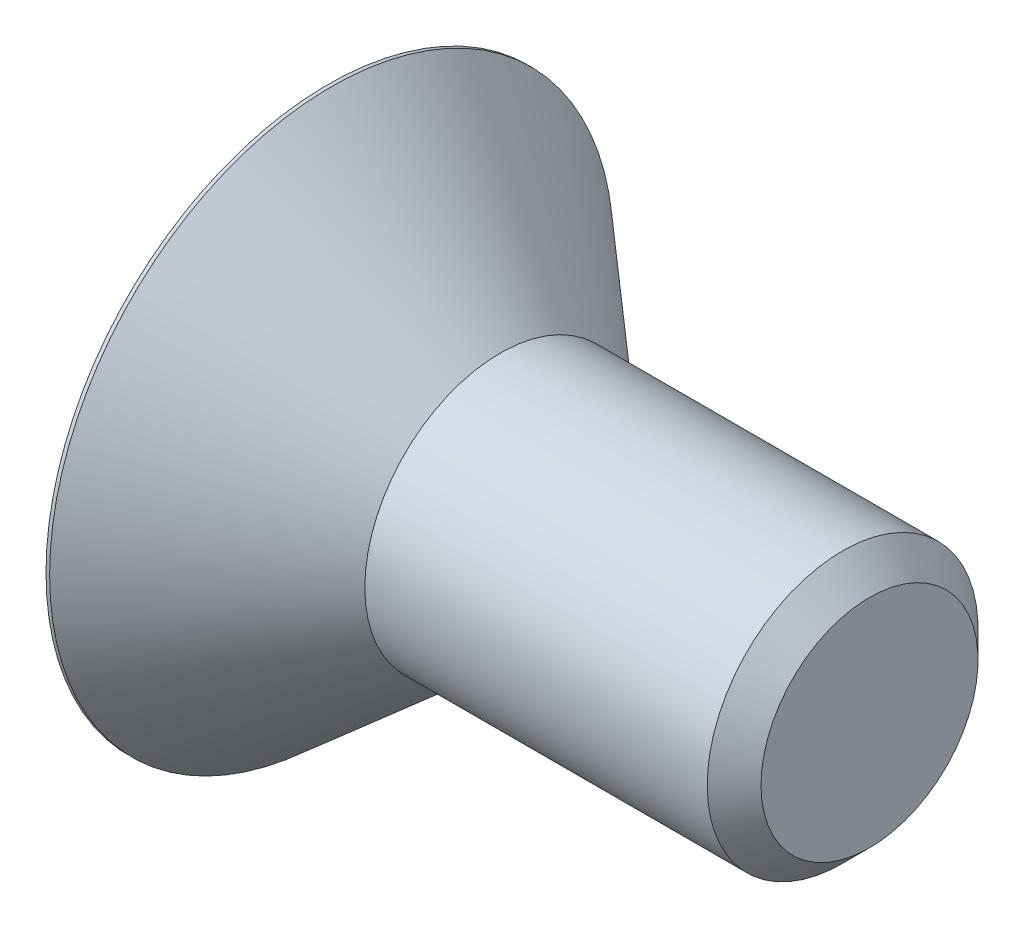
SolidWorks part; units mm, degrees
ref_plane "Plane1"
ref_plane "Plane2" through (0, 0, 0) normal (0, 1, 0) x (1, 0, 0)
ref_plane "Plane3" through (0, 0, 0) normal (1, 0, 0) x (0, 0, -1)
sketch "BodySke" plane through (0, 0, 0) normal (0, 0, 1) x (1, 0, 0)
  line L0 (0, 0) -> (0, 9.9187)
  line L1 (0.127, 9.9187) -> (6.0585, 4.7625)
  line L2 (0, 9.9187) -> (0.127, 9.9187)
  line L3 (6.0585, 4.7625) -> (18.1039, 4.7625)
  line L4 (19.05, 3.8163) -> (19.05, 0)
  line L5 (19.05, 0) -> (0, 0)
  line L6 (0, 0) -> (127, 0) construction
  line L7 (0.127, -9.9187) -> (6.0585, -4.7625) construction
  line L8 (19.05, 3.8163) -> (18.1039, 4.7625)
  line L9 (0, -9.9187) -> (0.127, -9.9187) construction
  line L10 (19.05, -3.8163) -> (18.1039, -4.7625) construction
  line L11 (7.646, 11.1125) -> (7.646, -11.1125) construction
  line L12 (0, 19.05) -> (0, -3.175) construction
  dimension "D1" = 0.127
  dimension "Diameter" = 9.525
  dimension "Length" = 19.05
  dimension "Body_ch_ang" = 45
  dimension "Head_dia" = 19.8374
  dimension "Minor_dia" = 7.6327
  dimension "Head_ang" = 82
  dimension "Advance" = 1.5875
  dimension "Thread_nom" = 19.05
revolve "BaseBody" add sketch "BodySke" angle 360 about L6
cosmetic thread "ThreadCosmetic" [suppressed] parameters "Thread_length"=11.531, "Thread_minor"=7.6327
sketch "Sketch2" plane through (0, 0, 0) normal (0, 0, 1) x (1, 0, 0)
  line L0 (0, 2.7788) -> (4.0386, 2.7788)
  line L1 (4.0386, 2.7788) -> (5.6429, 0)
  line L2 (0, 0) -> (127, 0) construction
  line L3 (5.6429, 0) -> (0, 0)
  line L4 (0, 0) -> (0, 2.7788)
  line L5 (0, -2.7788) -> (4.0386, -2.7788) construction
  line L6 (0, 0) -> (47.625, 0) construction
  line L8 (0, 9.9187) -> (0, -9.9187) construction
  dimension "D2" = 60
  dimension "PreBroach_depth" = 4.0386
  dimension "PreBroach_dia" = 5.5575
revolve "PreBroach" cut sketch "Sketch2" angle 360 about L6
sketch "Sketch3" plane through (0, 0, 0) normal (-1, 0, 0) x (0, 0, 1)
  line L0 (-2.7788, -1.6043) -> (-2.7788, 1.6043)
  line L1 (-2.7788, 1.6043) -> (0, 3.2086)
  line L2 (0, 3.2086) -> (2.7788, 1.6043)
  line L3 (2.7788, 1.6043) -> (2.7788, -1.6043)
  line L4 (2.7788, -1.6043) -> (0, -3.2086)
  line L5 (0, -3.2086) -> (-2.7788, -1.6043)
  dimension "D1" = 2.7788
  dimension "D2" = 2.7788
  dimension "D3" = 5.5575
  dimension "Hex_size" = 5.5575
extrude "Hex" cut sketch "Sketch3" against normal blind 4.0386
sketch "Sketch4" plane through (0, 0, 0) normal (-1, 0, 0) x (0, 0, 1)
  line L0 (0, 0) -> (3.2512, 0)
  line L1 (0, 0) -> (6.1484, 3.5498) construction
  line L2 (0, 0) -> (1.6256, 2.8156)
  line L3 (2.7204, 0.6907) -> (3.1182, 0.9204)
  line L4 (1.9584, 2.0106) -> (2.3562, 2.2402)
  arc A0 (2.7204, 0.6907) -> (1.9584, 2.0106) centre (0, 0) ccw
  arc A1 (3.2512, 0) -> (3.1182, 0.9204) centre (0, 0) ccw
  arc A2 (1.6256, 2.8156) -> (2.3562, 2.2402) centre (0, 0) cw
  dimension "D1" = 30
  dimension "Spline_n_dim" = 5.6134
  dimension "Spline_m_dim" = 6.5024
  dimension "D2" = 60
  dimension "D3" = 0.762
  dimension "Spline_p_dim" = 1.524
extrude "Spline" [suppressed] cut sketch "Sketch4" against normal blind 4.0386
pattern_circular "CirPattern1" [suppressed] count 6 every 60 about axis through (0, 0, 0) along (1, 0, 0)
sketch "ThdSchSke" plane through (0, 0, 0) normal (0, 0, 1) x (1, 0, 0)
  line L0 (7.5191, -3.8163) -> (6.8566, -4.7625)
  line L1 (7.5191, -3.8163) -> (8.1816, -4.7625)
  line L2 (8.1816, -4.7625) -> (8.1816, -5.9531)
  line L3 (-3.175, 0) -> (5.1513, 0) construction
  line L4 (0, 9.9187) -> (0, -9.9187) construction
  line L5 (8.1816, -5.9531) -> (6.8566, -5.9531)
  line L6 (6.8566, -5.9531) -> (6.8566, -4.7625)
  dimension "Thread_minor" = 7.6327
  dimension "Diameter" = 9.525
  dimension "Start" = 7.5191
  dimension "SideAngle" = 55
  dimension "VeeAngle" = 70
  dimension "Overcut" = 11.9063
revolve "ThreadSchematic" [suppressed] cut sketch "ThdSchSke" angle 360 about L3
pattern_linear "ThdSchPat" [suppressed]
equation "\"D3@Sketch4\" = \"Spline_p_dim@Sketch4\" / 2"
equation "\"Thread_minor@ThreadCosmetic\"  =  \"Minor_dia@BodySke\""
equation "\"D2@CirPattern1\" = 360 / \"Num_teeth@CirPattern1\""
equation "\"D1@Sketch3\" = \"Hex_size@Sketch3\" / 2"
equation "\"D2@Sketch3\" = \"D1@Sketch3\""
equation "\"D3@Sketch3\" = \"Hex_size@Sketch3\""
equation "\"Thread_length@ThreadCosmetic\" = ((sgn( (\"Length@BodySke\" - \"Advance@BodySke\" - ( ( ( \"Head_dia@BodySke\" - \"Diameter@BodySke\" ) * 0.5 ) / tan( \"Head_ang@BodySke\" * 0.008726646 ) ) ) - \"Thread_nom@BodySke\" )-1)*( (\"Length@BodySke\" - \"Advance@BodySke\" - ( ( ( \"Head_dia@BodySke\" - \"Diameter@BodySke\" ) * 0.5 ) / tan( \"Head_ang@BodySke\" * 0.008726646 ) ) ) - \"Thread_nom@BodySke\" ))/-2+ \"Thread_nom@BodySke\""
equation "\"Thread_minor@ThdSchSke\" = \"Minor_dia@BodySke\""
equation "\"Diameter@ThdSchSke\" = \"Diameter@BodySke\""
equation "\"Overcut@ThdSchSke\" = \"Diameter@BodySke\" * 1.25"
equation "\"Start@ThdSchSke\" = 0.000001 + \"Length@BodySke\" - \"Thread_length@ThreadCosmetic\"  '---Countersunk---"
equation "\"Num_threads@ThdSchPat\" = int( \"Thread_length@ThreadCosmetic\" / \"Advance@BodySke\" + 0.999 )  + 1"
equation "\"Advance@ThdSchPat\" = \"Thread_length@ThreadCosmetic\" /  (\"Num_threads@ThdSchPat\" - 1) 'relax it"
equation "\"Num_threads@ThdSchPat\" = \"Num_threads@ThdSchPat\" - sgn( \"Num_threads@ThdSchPat\" - 1) '---chamfered tips only---"
